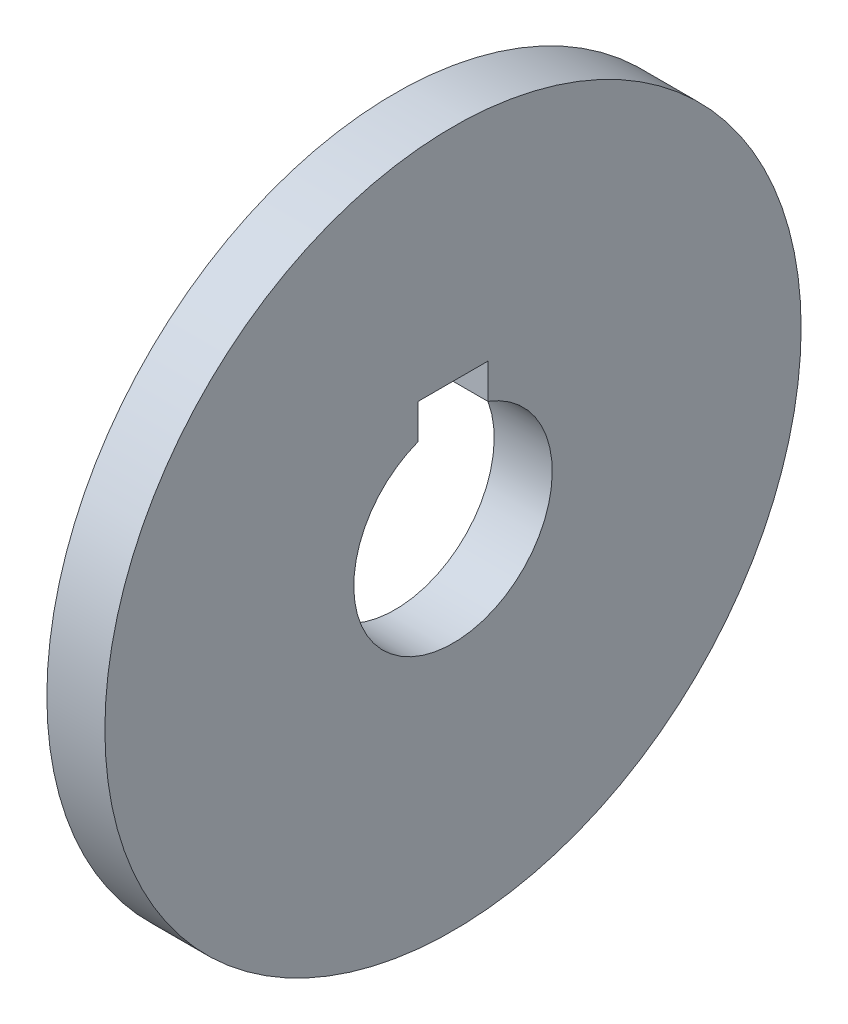
SolidWorks part; units mm, degrees
material "Alloy Steel"
ref_plane "Front Plane" through (0, 0, 0) normal (0, 0, 1) x (1, 0, 0)
ref_plane "Top Plane" through (0, 0, 0) normal (0, 1, 0) x (1, 0, 0)
ref_plane "Right Plane" through (0, 0, 0) normal (1, 0, 0) x (0, 0, -1)
sketch "Sketch1" plane through (0, 0, 0) normal (1, 0, 0) x (0, 0, -1)
  circle A0 centre (0, 0) radius 30
  dimension "D1" = 60
extrude "Boss-Extrude1" add sketch "Sketch1" along normal mid plane 5
sketch "Sketch8" plane through (2.5, 0, 0) normal (1, 0, 0) x (0, 0, -1)
  line L0 (0, 5.55) -> (0, 8.55) construction
  line L10 (0, 8.55) -> (0, 11.0064) construction
  line L11 (0, 11.0064) -> (-3, 11.0064)
  line L14 (-3, 11.0064) -> (-3, 8.0064)
  line L15 (0, 11.0064) -> (3, 11.0064)
  line L16 (3, 11.0064) -> (3, 8.0064)
  line L17 (-3, 8.0064) -> (3, 8.0064) construction
  arc A1 (-3, 8.0064) -> (3, 8.0064) centre (0, 0) ccw
  dimension "D1" = 17.1
  dimension "D2" = 3
  dimension "D3" = 3
extrude "Cut-Extrude4" cut sketch "Sketch8" against normal through all
